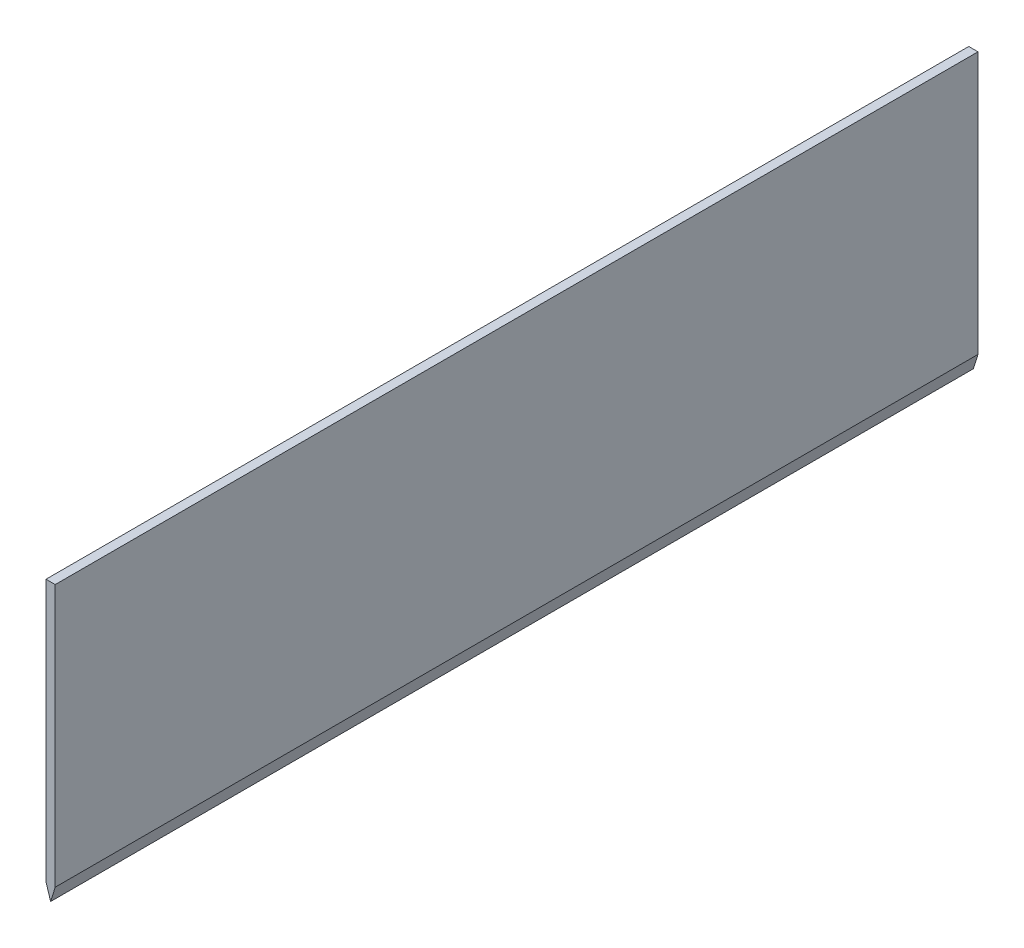
SolidWorks part; units mm, degrees
material "201 Acero inoxidable recocido (SS)"
ref_plane "Alzado" through (0, 0, 0) normal (0, 0, 1) x (1, 0, 0)
ref_plane "Planta" through (0, 0, 0) normal (0, 1, 0) x (1, 0, 0)
ref_plane "Vista lateral" through (0, 0, 0) normal (1, 0, 0) x (0, 0, -1)
sketch "Croquis1" plane through (0, 0, 0) normal (0, 0, 1) x (1, 0, 0)
  line L0 (0, -15) -> (0.5, -13.4024)
  line L1 (-0.5, 15) -> (0.5, 15)
  line L2 (-0.5, 15) -> (-0.5, -13.4024)
  line L3 (-0.4467, -13.4024) -> (-0.5, -13.4024)
  line L4 (0.5, 15) -> (0.5, -13.4024)
  line L5 (-0.5, 15) -> (0.5, -15) construction
  line L6 (-0.5, -15) -> (0.5, 15) construction
  line L7 (0.5, -13.4024) -> (0.4467, -13.4024)
  line L8 (-0.5, -13.4024) -> (0, -15)
  point P0 (0, 0)
  dimension "D1" = 30
  dimension "D2" = 1
extrude "Saliente-Extruir1" add sketch "Croquis1" along normal mid plane 100
